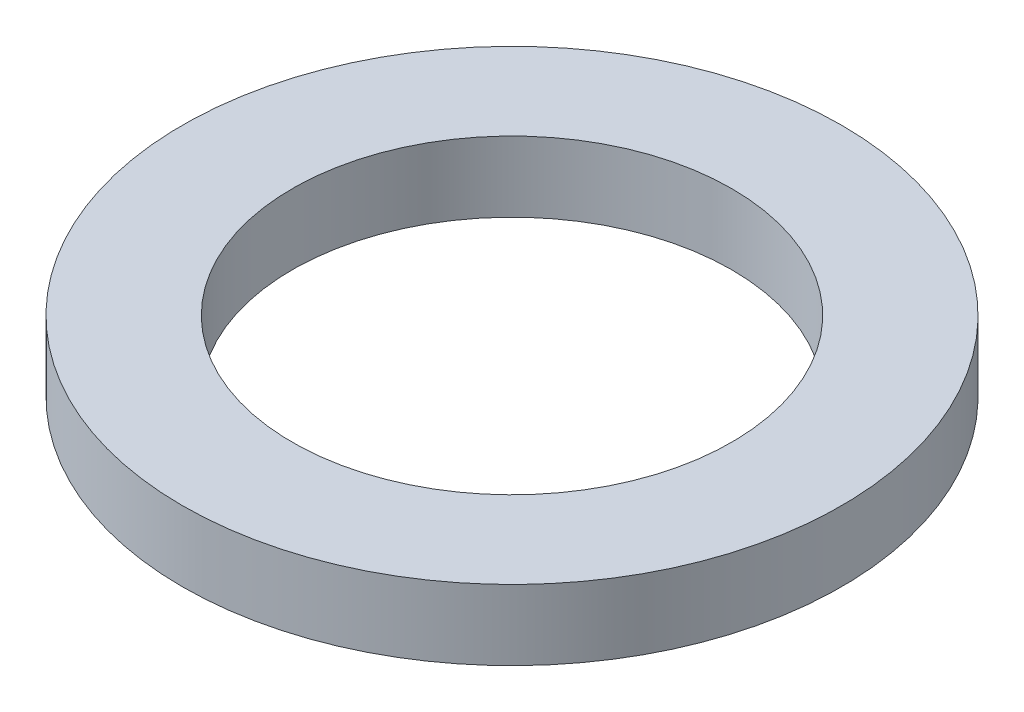
SolidWorks part; units mm, degrees
material "Brass"
ref_plane "Front Plane" through (0, 0, 0) normal (0, 0, 1) x (1, 0, 0)
ref_plane "Top Plane" through (0, 0, 0) normal (0, 1, 0) x (1, 0, 0)
ref_plane "Right Plane" through (0, 0, 0) normal (1, 0, 0) x (0, 0, -1)
sketch "Sketch1" plane through (0, 0, 0) normal (0, 1, 0) x (1, 0, 0)
  circle A0 centre (0, 0) radius 1
  circle A1 centre (0, 0) radius 1.5
  dimension "D1" = 3
  dimension "D2" = 2
extrude "Boss-Extrude1" add sketch "Sketch1" along normal blind 0.32
